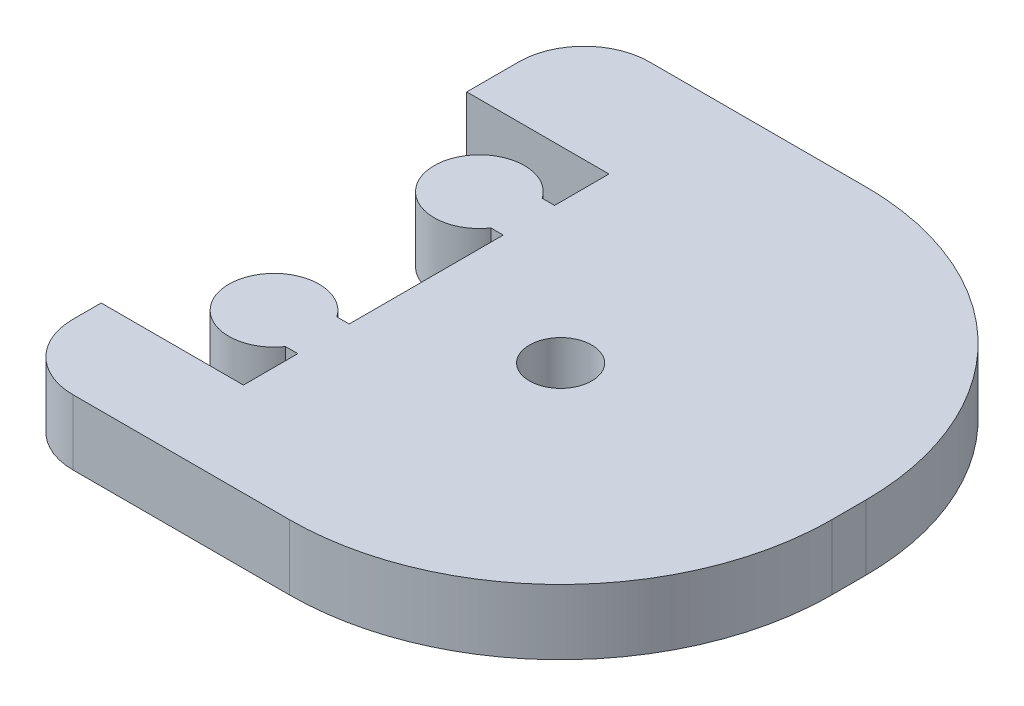
SolidWorks part; units mm, degrees
ref_plane "Front Plane" through (0, 0, 0) normal (0, 0, 1) x (1, 0, 0)
ref_plane "Top Plane" through (0, 0, 0) normal (0, 1, 0) x (1, 0, 0)
ref_plane "Right Plane" through (0, 0, 0) normal (1, 0, 0) x (0, 0, -1)
sketch "Sketch1" plane through (0, 0, 0) normal (0, 1, 0) x (1, 0, 0)
  line L1 (-25.4, 10.795) -> (25.4, 10.795)
  line L2 (-25.4, 10.795) -> (-25.4, -10.795)
  line L3 (-25.4, -10.795) -> (25.4, -10.795)
  line L4 (25.4, 10.795) -> (25.4, -10.795)
  dimension "D1" = 21.59
  dimension "D2" = 50.8
  dimension "D3" = 10.795
  dimension "D4" = 25.4
extrude "Boss-Extrude1" add sketch "Sketch1" along normal blind 3.175
fillet "Fillet1" radius 10.16 2 edges at (-25.4, 1.5875, 10.795) (25.4, 1.5875, 10.795)
sketch "Sketch3" plane through (0, 3.175, 0) normal (0, 1, 0) x (1, 0, 0)
  line L0 (-7.7526, -0.635) -> (18.5521, -0.635) construction
  circle A0 centre (15.24, -0.635) radius 1.1671
  arc A2 (15.24, -10.795) -> (25.4, -0.635) centre (15.24, -0.635) ccw construction
  circle A3 centre (-3.81, -0.635) radius 1.1671
  dimension "D1" = 2.3343
  dimension "D6" = 2.3343
  dimension "D5" = 19.05
extrude "Cut-Extrude1" cut sketch "Sketch3" against normal through all
fillet "Fillet3" radius 10.16 2 edges at (-25.4, 1.5875, -10.795) (25.4, 1.5875, -10.795)
scale "Scale1" scale about centroid uniform scaling no x scale factor 1.3 y scale factor 1 z scale factor 1.3
sketch "Sketch4" plane through (0, 3.175, 0) normal (0, 1, 0) x (1, 0, 0)
  line L0 (19.8267, 14.0319) -> (-19.7973, 14.0319) construction
  line L1 (6.1107, 14.0319) -> (-33.0053, 14.0319)
  line L2 (6.1107, 14.0319) -> (6.1107, -14.0351)
  line L3 (6.1107, -14.0351) -> (-33.0053, -14.0351)
  line L4 (-33.0053, 14.0319) -> (-33.0053, -14.0351)
  line L5 (-19.7973, -14.0351) -> (19.8267, -14.0351) construction
  line L6 (-33.0053, 0.8239) -> (-33.0053, -0.8271) construction
  line L8 (33.0347, -0.8271) -> (33.0347, 0.8239) construction
  dimension "D1" = 26.924
extrude "Cut-Extrude2" cut sketch "Sketch4" against normal through all
sketch "Sketch5" plane through (0, 3.175, 0) normal (0, 1, 0) x (1, 0, 0)
  line L0 (13.0358, -6.8306) -> (13.0358, -9.4806)
  line L2 (13.0358, 5.6694) -> (13.0358, 8.3194)
  line L4 (13.0358, 3.1694) -> (13.0358, -4.3306)
  line L5 (12.4358, -4.3306) -> (13.0358, -4.3306)
  line L6 (12.4358, -6.8306) -> (13.0358, -6.8306)
  line L7 (12.4358, 3.1694) -> (13.0358, 3.1694)
  line L8 (12.4358, 5.6694) -> (13.0358, 5.6694)
  line L9 (12.0358, 8.3194) -> (6.0358, 8.3194) construction
  line L10 (13.0358, 8.3194) -> (6.1107, 8.3194)
  line L11 (6.1107, -14.0351) -> (6.1107, 14.0319) construction
  line L12 (13.0358, -9.4806) -> (6.1107, -9.4806)
  line L13 (6.1107, 8.3194) -> (6.1107, -9.4806)
  line L14 (12.0358, -9.4806) -> (6.0358, -9.4806) construction
  arc A0 (12.4358, 5.6694) -> (12.4358, 3.1694) centre (10.6254, 4.4194) ccw
  arc A1 (12.4358, -4.3306) -> (12.4358, -6.8306) centre (10.6254, -5.5806) ccw
  dimension "D1" = 2.2
  dimension "D2" = 2.2
extrude "Cut-Extrude3" cut sketch "Sketch5" against normal through all
fillet "Fillet5" radius 3.175 2 edges at (6.1107, 1.5875, -14.0319) (6.1107, 1.5875, 14.0351)
equation "\"D4@Sketch1\"=\"D2@Sketch1\"/2"
equation "\"D3@Sketch1\"=\"D1@Sketch1\"/2"
